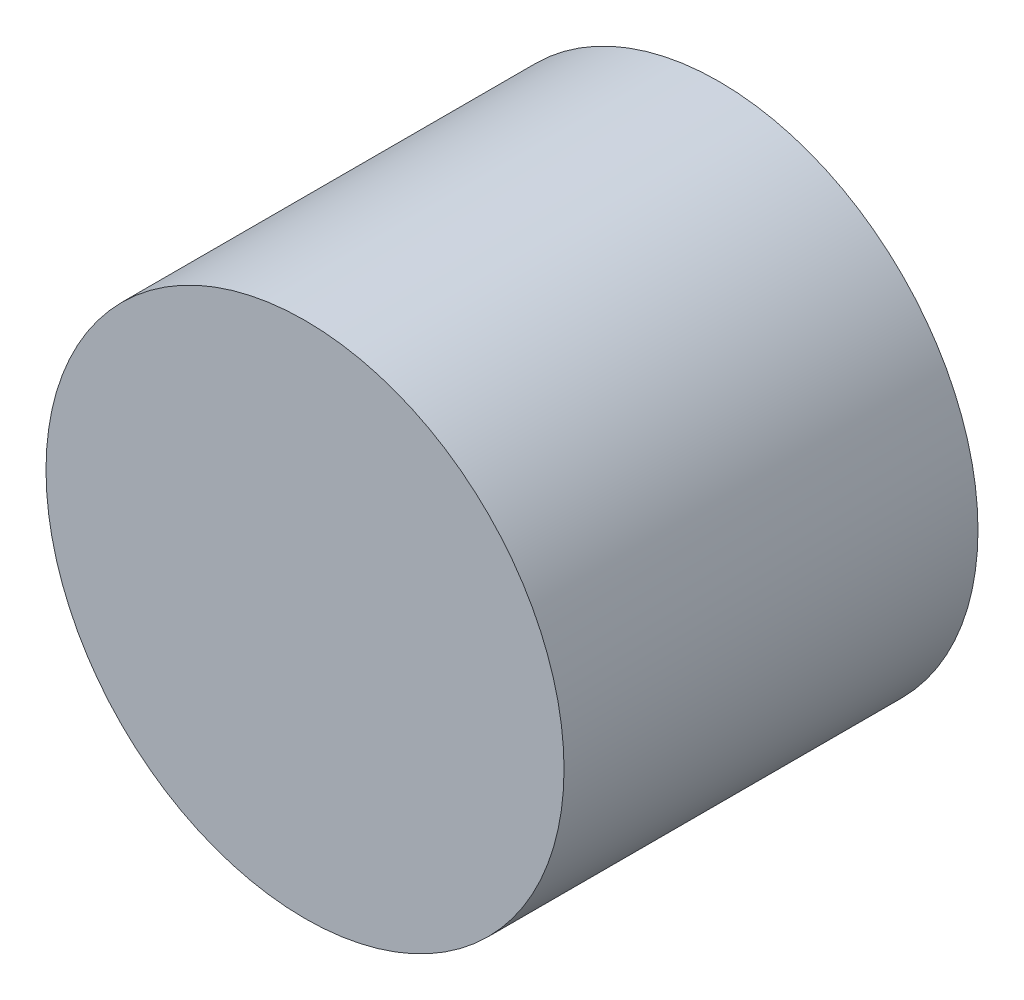
SolidWorks part; units mm, degrees
ref_plane "前视基准面" through (0, 0, 0) normal (0, 0, 1) x (1, 0, 0)
ref_plane "上视基准面" through (0, 0, 0) normal (0, 1, 0) x (1, 0, 0)
ref_plane "右视基准面" through (0, 0, 0) normal (1, 0, 0) x (0, 0, -1)
sketch "草图2" plane through (0, 0, 0) normal (0, 0, 1) x (1, 0, 0)
  circle A0 centre (0, 0) radius 62.5696
extrude "凸台-拉伸2" add sketch "草图2" along normal blind 100 contours A0
sketch3d "3D草图2"
  circle A0 centre (0, 0, 100) radius 62.5696 construction
  circle A1 centre (0, 0, 100) radius 62.5696
  point P2 (0, 0, 162.5696)
  point P4 (0, 0, 162.5696)
sketch "草图3" plane through (0, 0, 100) normal (0, 0, 1) x (1, 0, 0)
  line L0 (-102.0149, 56.091) -> (-99.4301, -11.4594)
  line L1 (-112.0076, 55.7086) -> (-109.4228, -11.8418)
  circle A4 centre (0, 0) radius 57.5696
  circle A5 centre (0, 0) radius 57.5696
  circle A7 centre (0, 0) radius 52.5696
  circle A8 centre (0, 0) radius 52.5696
  dimension "D1" = 5
  dimension "D2" = 10
  dimension "D3" = 10
